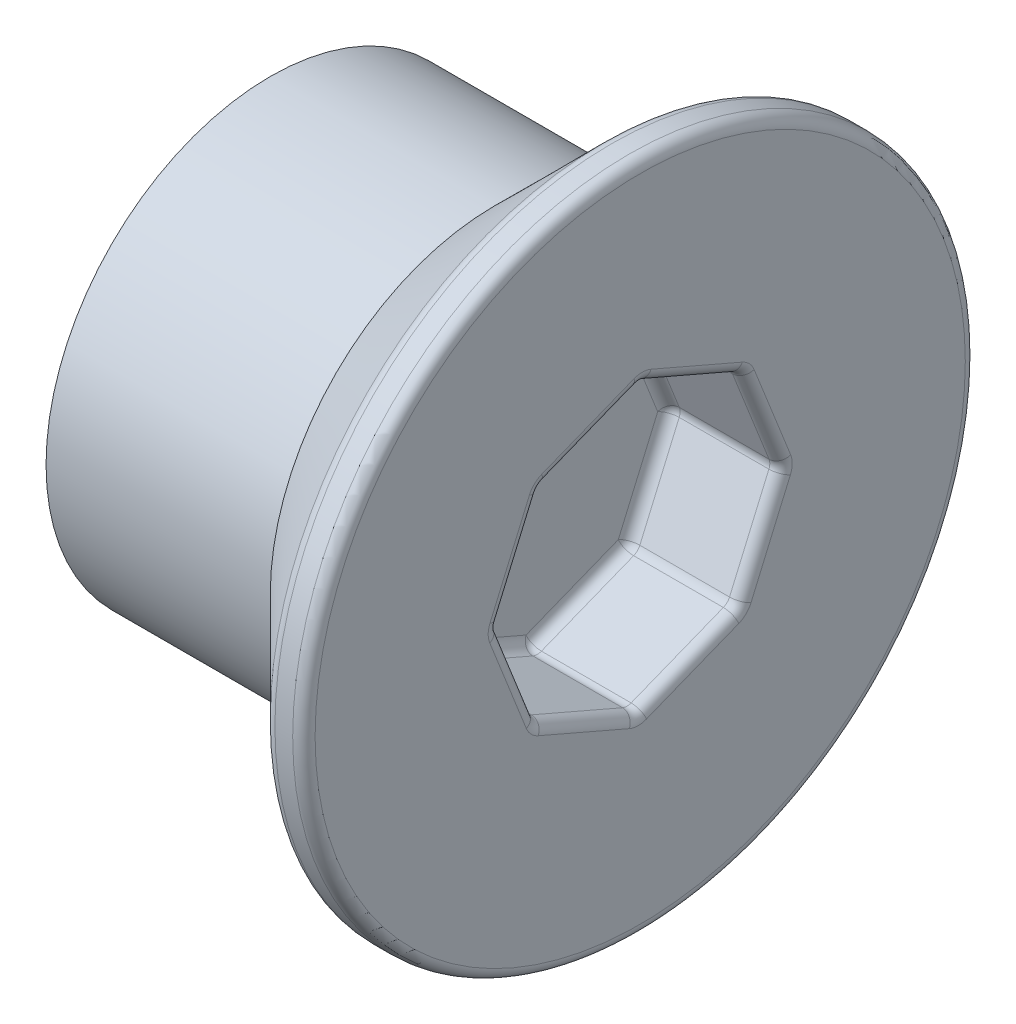
SolidWorks part; units mm, degrees
material "moto_black"
ref_plane "Front Plane" through (0, 0, 0) normal (0, 0, 1) x (1, 0, 0)
ref_plane "Top Plane" through (0, 0, 0) normal (0, 1, 0) x (1, 0, 0)
ref_plane "Right Plane" through (0, 0, 0) normal (1, 0, 0) x (0, 0, -1)
sketch "Sketch1" plane through (0, 0, 0) normal (1, 0, 0) x (0, 0, -1)
  circle A0 centre (0, 0) radius 3
  dimension "D1" = 6
extrude "Boss-Extrude1" add sketch "Sketch1" along normal blind 1.3
chamfer "Chamfer1" distance 1 angle 45 1 edges at (0, 0, -3)
sketch "Sketch2" plane through (0, 0, 0) normal (-1, 0, 0) x (0, 0, 1)
  circle A2 centre (0, 0) radius 2
  circle A3 centre (0, 0) radius 2
  dimension "D1" = 0
extrude "Boss-Extrude2" add sketch "Sketch2" along normal blind 2
sketch "Sketch4" plane through (1.3, 0, 0) normal (1, 0, 0) x (0, 0, -1)
  line L0 (0.9078, 0.8802) -> (0.0195, 1.2643)
  line L1 (0.9078, 0.8802) -> (0.0195, 1.2643)
  line L2 (0.0195, 1.2643) -> (-0.8802, 0.9078)
  line L3 (-0.8802, 0.9078) -> (-1.2643, 0.0195)
  line L4 (-1.2643, 0.0195) -> (-0.9078, -0.8802)
  line L5 (-0.9078, -0.8802) -> (-0.0195, -1.2643)
  line L6 (-0.0195, -1.2643) -> (0.8802, -0.9078)
  line L7 (0.8802, -0.9078) -> (1.2643, -0.0195)
  line L8 (1.2643, -0.0195) -> (0.9078, 0.8802)
  line L9 (0.0195, 1.2643) -> (-0.8802, 0.9078)
  line L10 (-0.8802, 0.9078) -> (-1.2643, 0.0195)
  line L11 (-1.2643, 0.0195) -> (-0.9078, -0.8802)
  line L12 (-0.9078, -0.8802) -> (-0.0195, -1.2643)
  line L13 (-0.0195, -1.2643) -> (0.8802, -0.9078)
  line L14 (0.8802, -0.9078) -> (1.2643, -0.0195)
  line L15 (1.2643, -0.0195) -> (0.9078, 0.8802)
  circle A1 centre (0, 0) radius 1.1682 construction
  circle A2 centre (0, 0) radius 3
  circle A3 centre (0, 0) radius 3
  dimension "D1" = 0
  dimension "D2" = 0
extrude "Cut-Extrude3" cut sketch "Sketch4" against normal blind 1 contours L7 L8 L0 L2 L3 L4 L5 L6
fillet "Fillet1" radius 0.1 24 edges at (1.3, -1.0723, 0.4636) (1.3, 0.4636, 1.0723) (1.3, 1.0723, -0.4636) (0.8, 0.8802, -0.9078) (1.3, 0.4303, -1.086) (0.8, -0.0195, -1.2643) (1.3, -0.4636, -1.0723) (0.8, -1.2643, 0.0195) (0.8, -0.9078, -0.8802) (1.3, -1.086, -0.4303) (0.8, 0.0195, 1.2643) (0.8, -0.8802, 0.9078) (1.3, -0.4303, 1.086) (0.8, 1.2643, -0.0195) (0.8, 0.9078, 0.8802) (1.3, 1.086, 0.4303) (0.3, -1.086, -0.4303) (0.3, -1.0723, 0.4636) (0.3, -0.4303, 1.086) (0.3, 0.4636, 1.0723) (0.3, 1.086, 0.4303) (0.3, 1.0723, -0.4636) (0.3, 0.4303, -1.086) (0.3, -0.4636, -1.0723)
fillet "Fillet2" radius 0.1 2 edges at (1, 0, -3) (1.3, 0, -3)
